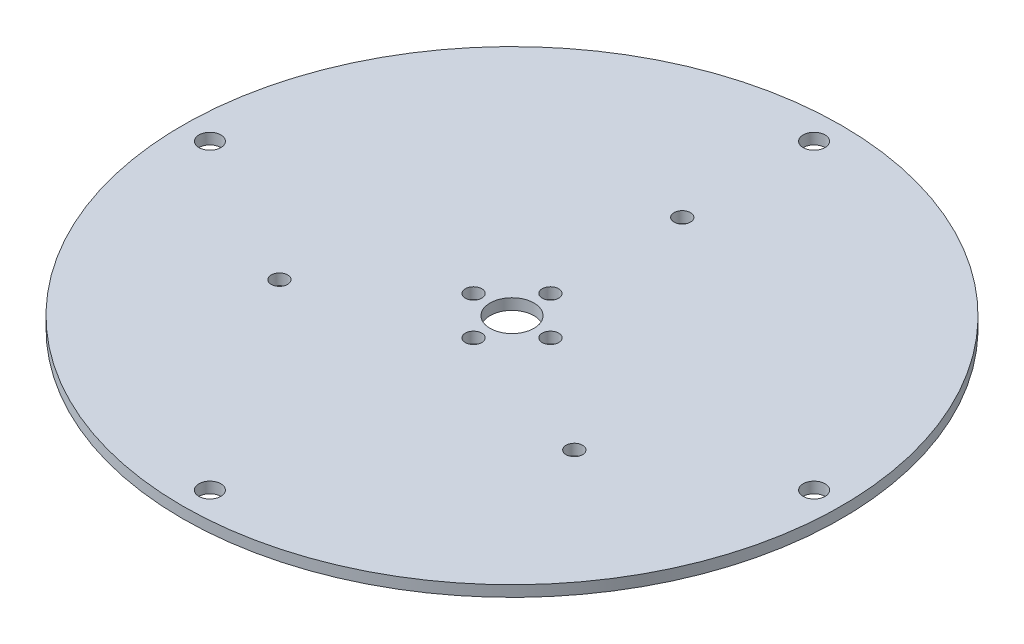
SolidWorks part; units mm, degrees
ref_plane "前视基准面" through (0, 0, 0) normal (0, 0, 1) x (1, 0, 0)
ref_plane "上视基准面" through (0, 0, 0) normal (0, 1, 0) x (1, 0, 0)
ref_plane "右视基准面" through (0, 0, 0) normal (1, 0, 0) x (0, 0, -1)
sketch "草图1" plane through (0, 0, 0) normal (0, 1, 0) x (1, 0, 0)
  circle A0 centre (0, 0) radius 60
  circle A4 centre (0, 31) radius 1.5
  circle A5 centre (26.8468, -15.5) radius 1.5
  circle A6 centre (-26.8468, -15.5) radius 1.5
  point P11 (0, 0)
  point P12 (0, 0)
  dimension "D1" = 3
extrude "凸台-拉伸1" add sketch "草图1" along normal blind 2
sketch "草图2" plane through (0, 2, 0) normal (0, 1, 0) x (1, 0, 0)
  circle A0 centre (0, 0) radius 4
  circle A5 centre (0, 7) radius 1.5
  circle A6 centre (7, 0) radius 1.5
  circle A7 centre (0, -7) radius 1.5
  circle A8 centre (-7, 0) radius 1.5
  point P14 (0, 0)
  point P15 (0, 0)
  dimension "D1" = 4
extrude "切除-拉伸1" cut sketch "草图2" against normal blind 2
sketch "草图3" plane through (0, 2, 0) normal (0, 1, 0) x (1, 0, 0)
  circle A0 centre (0, 55) radius 2
  circle A1 centre (55, 0) radius 2
  circle A2 centre (0, -55) radius 2
  circle A3 centre (-55, 0) radius 2
  point P13 (0, 0)
  dimension "D1" = 4
extrude "切除-拉伸2" cut sketch "草图3" against normal blind 10
